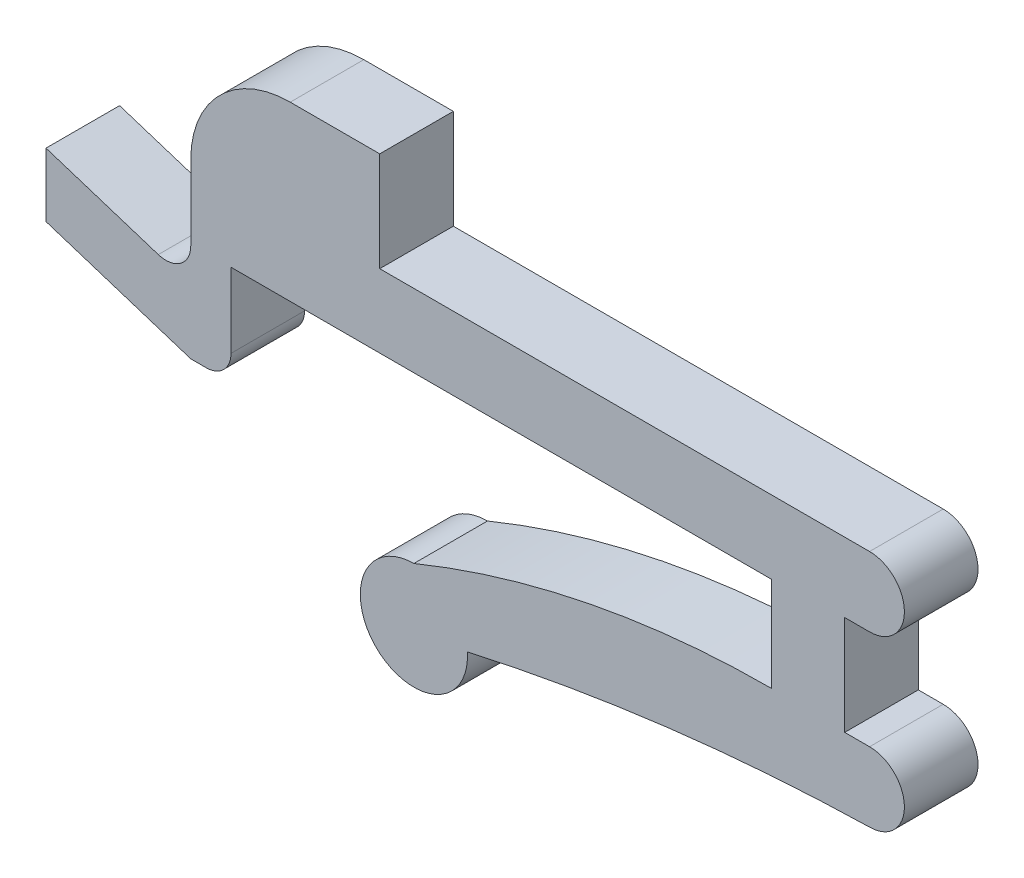
SolidWorks part; units mm, degrees
material "ABS"
ref_plane "Front Plane" through (0, 0, 0) normal (0, 0, 1) x (1, 0, 0)
ref_plane "Top Plane" through (0, 0, 0) normal (0, 1, 0) x (1, 0, 0)
ref_plane "Right Plane" through (0, 0, 0) normal (1, 0, 0) x (0, 0, -1)
sketch "Sketch1" plane through (0, 0, 0) normal (0, 0, 1) x (1, 0, 0)
  line L0 (0, 109.4204) -> (250.19, 109.4204)
  line L1 (0, 160.2204) -> (-96.52, 160.2204)
  line L2 (250.19, 73.8604) -> (237.49, 73.8604)
  line L3 (237.49, 73.8604) -> (237.49, 23.0604)
  line L4 (237.49, 23.0604) -> (250.19, 23.0604)
  line L5 (-96.52, 160.2204) -> (-96.52, 139.9016)
  line L6 (0, 109.4204) -> (0, 160.2204)
  line L7 (-96.52, 139.9016) -> (-96.52, 53.7944)
  line L8 (-96.52, 53.7944) -> (-170.4572, 77.5229)
  line L9 (-170.4572, 77.5229) -> (-170.4572, 45.0109)
  line L10 (-170.4572, 45.0109) -> (-96.52, 21.2824)
  line L12 (-75.9684, 72.0824) -> (200.152, 72.0824)
  line L13 (200.152, 72.0824) -> (200.152, 23.8224)
  line L15 (-75.9684, 21.2824) -> (-96.52, 21.2824)
  line L16 (-75.9684, 72.0824) -> (-75.9684, 21.2824)
  arc A0 (250.19, -12.4996) -> (44.7442, -37.7212) centre (274.5816, -1060.5404) ccw
  arc A1 (17.4419, -12.2514) -> (44.7442, -37.7212) centre (17.4419, -39.6196) ccw
  arc A2 (200.152, 23.8224) -> (17.4419, -12.2514) centre (200.152, -456.9191) ccw
  arc A3 (250.19, 73.8604) -> (250.19, 109.4204) centre (250.19, 91.6404) ccw
  arc A4 (250.19, -12.4996) -> (250.19, 23.0604) centre (250.19, 5.2804) ccw
  dimension "D9" = 37.338
  dimension "D1" = 250.19
  dimension "D2" = 35.56
  dimension "D3" = 12.7
  dimension "D4" = 50.8
  dimension "D5" = 35.56
  dimension "D6" = 37.338
  dimension "D7" = 37.338
  dimension "D8" = 48.26
  dimension "D10" = 32.512
  dimension "D11" = 96.52
  dimension "D12" = 50.8
  dimension "D13" = 50.8
extrude "Boss-Extrude1" add sketch "Sketch1" along normal blind 37.592 contours L0 A3 L2 L3 L4 A4 A0 A1 A2 L13 L12 L16 L15 L10 L9 L8 L7 L5 L1 L6
fillet "Fillet1" radius 12.7 1 edges at (-75.9684, 21.2824, 18.796)
fillet "Fillet2" radius 50.8 1 edges at (-96.52, 160.2204, 18.796)
fillet "Fillet3" radius 12.7 1 edges at (-96.52, 53.7944, 18.796)
scale "Scale1" bodies to scale 101 scale about centroid uniform scaling yes scale factor 0.05
